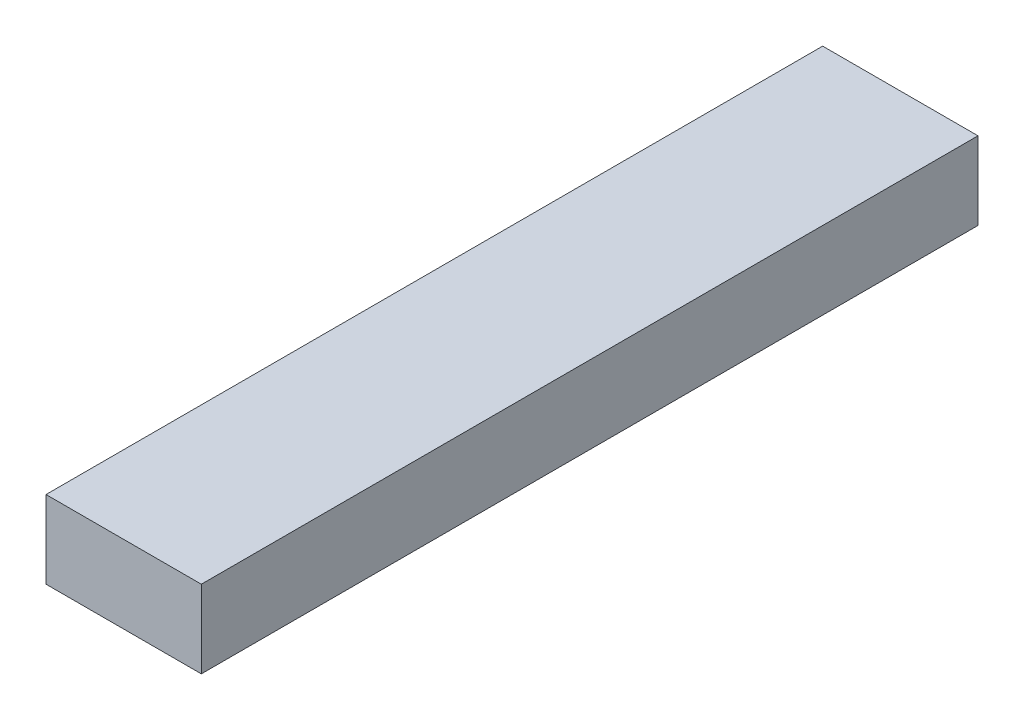
SolidWorks part; units mm, degrees
ref_plane "Piano frontale" through (0, 0, 0) normal (0, 0, 1) x (1, 0, 0)
ref_plane "Piano superiore" through (0, 0, 0) normal (0, 1, 0) x (1, 0, 0)
ref_plane "Piano destro" through (0, 0, 0) normal (1, 0, 0) x (0, 0, -1)
sketch "Schizzo1" plane through (0, 0, 0) normal (0, 0, 1) x (1, 0, 0)
  line L1 (100, -50) -> (-100, -50)
  line L2 (100, -50) -> (100, 50)
  line L3 (100, 50) -> (-100, 50)
  line L4 (-100, -50) -> (-100, 50)
  line L5 (100, -50) -> (-100, 50) construction
  line L6 (100, 50) -> (-100, -50) construction
  point P1 (0, 0)
  dimension "D1" = 200
  dimension "D2" = 100
extrude "Estrusione-Estrusione1" add sketch "Schizzo1" along normal blind 1000
